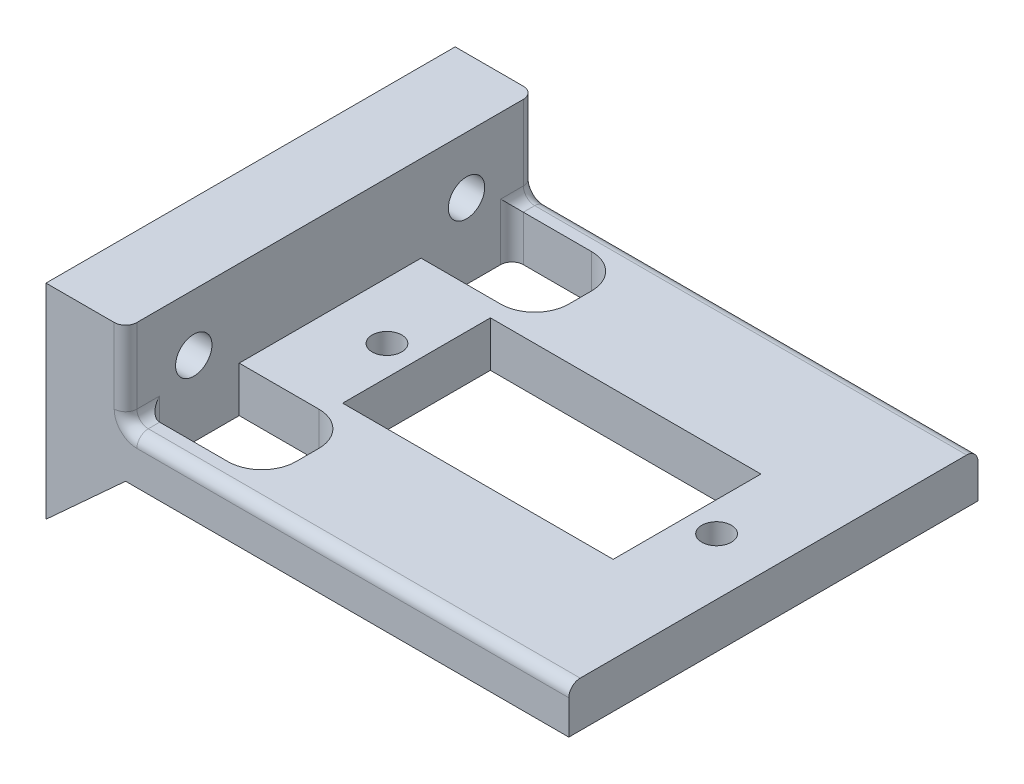
SolidWorks part; units mm, degrees
ref_plane "Front Plane" through (0, 0, 0) normal (0, 0, 1) x (1, 0, 0)
ref_plane "Top Plane" through (0, 0, 0) normal (0, 1, 0) x (1, 0, 0)
ref_plane "Right Plane" through (0, 0, 0) normal (1, 0, 0) x (0, 0, -1)
sketch "Servo_shelf_profile" plane through (0, 0, 0) normal (0, 1, 0) x (1, 0, 0)
  line L1 (-21, -18) -> (25, -18)
  line L2 (-21, -18) -> (-21, 18)
  line L3 (-21, 18) -> (25, 18)
  line L4 (25, -18) -> (25, 18)
  dimension "D1" = 46
  dimension "D2" = 36
  dimension "D3" = 25
  dimension "D4" = 18
extrude "Servo_shelf" add sketch "Servo_shelf_profile" along normal blind 4 from offset 21.4
sketch "Rear_clamping_block_profile" plane through (0, 0, 0) normal (0, 0, 1) x (1, 0, 0)
  line L1 (-21, 23) -> (-14, 23)
  line L2 (-21, 23) -> (-21, 33)
  line L3 (-21, 33) -> (-14, 33)
  line L4 (-14, 23) -> (-14, 33)
  dimension "D1" = 7
  dimension "D2" = 10
  dimension "D3" = 14
  dimension "D4" = 23
extrude "Rear_clamping_block" add sketch "Rear_clamping_block_profile" along normal blind 36 from offset 18
sketch "Servo_body_window_profile" plane through (0, 0, 0) normal (0, 1, 0) x (1, 0, 0)
  line L1 (-6.4, -6.5) -> (17.4, -6.5)
  line L2 (-6.4, -6.5) -> (-6.4, 6.5)
  line L3 (-6.4, 6.5) -> (17.4, 6.5)
  line L4 (17.4, -6.5) -> (17.4, 6.5)
  dimension "D1" = 23.8
  dimension "D2" = 13
  dimension "D3" = 17.4
  dimension "D4" = 6.5
extrude "Servo_body_window" cut sketch "Servo_body_window_profile" along normal through all from offset 20.4
sketch "Yaw_servo_M2_fasteners_profile" plane through (0, 0, 0) normal (0, 1, 0) x (1, 0, 0)
  circle A0 centre (-9, 0) radius 1.3
  circle A1 centre (20, 0) radius 1.3
  dimension "D1" = 2.6
  dimension "D2" = 2.6
  dimension "D3" = 20
  dimension "D4" = 9
extrude "Yaw_servo_M2_fasteners" cut sketch "Yaw_servo_M2_fasteners_profile" along normal through all from offset 20.4
sketch "Left_nut_access_profile" plane through (0, 0, 0) normal (0, 1, 0) x (1, 0, 0)
  line L1 (-14, 8) -> (-4, 8)
  line L2 (-14, 8) -> (-14, 16)
  line L3 (-14, 16) -> (-4, 16)
  line L4 (-4, 8) -> (-4, 16)
  dimension "D1" = 10
  dimension "D2" = 8
  dimension "D3" = 4
  dimension "D4" = 8
extrude "Left_nut_access" cut sketch "Left_nut_access_profile" along normal through all from offset 20
sketch "Right_nut_access_profile" plane through (0, 0, 0) normal (0, 1, 0) x (1, 0, 0)
  line L1 (-14, -16) -> (-4, -16)
  line L2 (-14, -16) -> (-14, -8)
  line L3 (-14, -8) -> (-4, -8)
  line L4 (-4, -16) -> (-4, -8)
  dimension "D1" = 10
  dimension "D2" = 8
  dimension "D3" = 4
  dimension "D4" = 8
extrude "Right_nut_access" cut sketch "Right_nut_access_profile" along normal through all from offset 20
sketch "Rear_clamping_M3_profile" plane through (0, 0, 0) normal (1, 0, 0) x (0, 0, -1)
  circle A0 centre (12, 28) radius 1.6
  circle A1 centre (-12, 28) radius 1.6
  dimension "D1" = 3.2
  dimension "D2" = 3.2
  dimension "D3" = 12
  dimension "D4" = 12
  dimension "D5" = 28
extrude "Rear_clamping_M3_holes" cut sketch "Rear_clamping_M3_profile" along normal blind 11 from offset 25
fillet "Fillet1" radius 3 4 edges at (-4, 23.4, 16) (-4, 23.4, 8) (-4, 23.4, -16) (-4, 23.4, -8)
fillet "Fillet2" radius 1 8 edges at (-14, 25.4, -17) (-14, 25.4, 17) (-14, 23.4, 16) (-14, 23.4, -16) (-14, 29.2, -18) (-14, 29.2, 18) (5.5, 25.4, 18) (5.5, 25.4, -18)
sketch "Sketch1" plane through (0, 0, -18) normal (0, 0, -1) x (-1, 0, 0)
  line L0 (14, 21.4) -> (21, 15)
  line L1 (21, 15) -> (21, 21.4)
  line L2 (21, 21.4) -> (14, 21.4)
extrude "Boss-Extrude1" add sketch "Sketch1" against normal up to surface (36 mm away) contours L0 L1 L2
